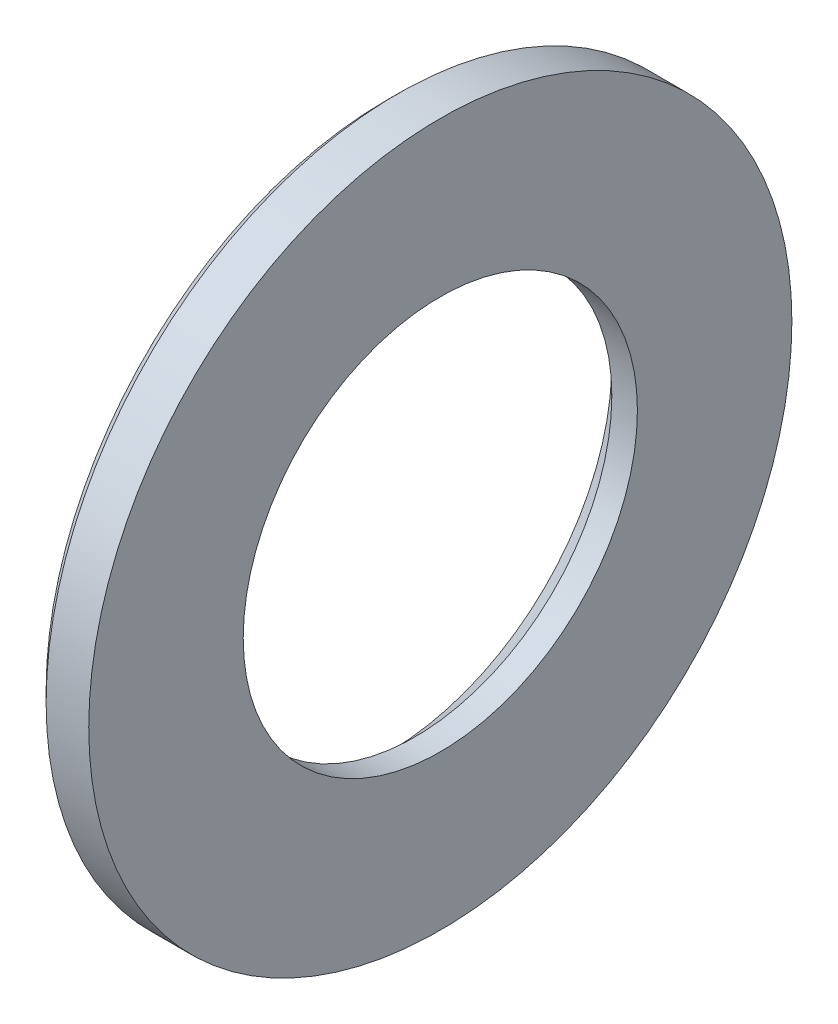
SolidWorks part; units mm, degrees
ref_plane "Plane1" through (0, 0, 0) normal (0, 0, 1) x (1, 0, 0)
ref_plane "Plane2" through (0, 0, 0) normal (0, 1, 0) x (1, 0, 0)
ref_plane "Plane3" through (0, 0, 0) normal (1, 0, 0) x (0, 0, -1)
sketch "Sketch1" plane through (0, 0, 0) normal (0, 0, 1) x (1, 0, 0)
  line L0 (-34.925, 0) -> (9.525, 0) construction
  line L1 (0, 18.5) -> (0, 33)
  line L2 (0, 33) -> (-4, 33)
  line L3 (-5, 32) -> (-5, 21.1)
  line L4 (-2.4, 18.5) -> (0, 18.5)
  line L5 (-5, 32) -> (-4, 33)
  line L7 (-2.4, 18.5) -> (-5, 21.1)
  dimension "D1" = 45
  dimension "D2" = 45
  dimension "Thickness" = 5
  dimension "Inside_dia" = 37
  dimension "Outside_dia" = 66
  dimension "OD_ch_ht" = 1
  dimension "ID_ch_ht" = 2.6
revolve "Base-Revolve" add sketch "Sketch1" angle 360 about L0
